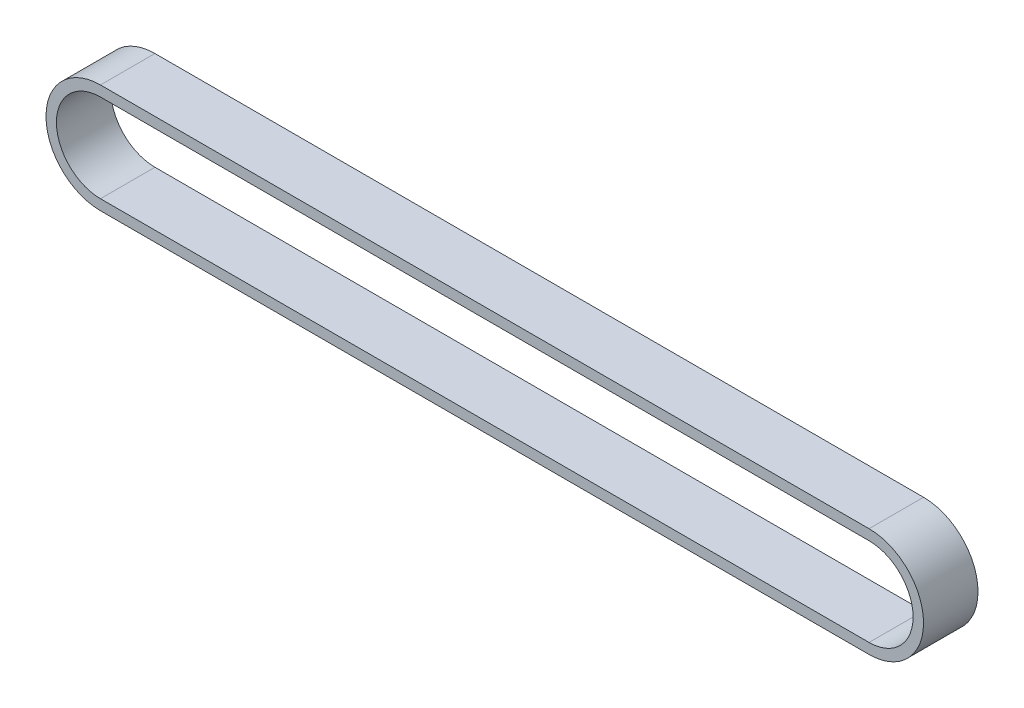
SolidWorks part; units mm, degrees
ref_plane "Front Plane" through (0, 0, 0) normal (0, 0, 1) x (1, 0, 0)
ref_plane "Top Plane" through (0, 0, 0) normal (0, 1, 0) x (1, 0, 0)
ref_plane "Right Plane" through (0, 0, 0) normal (1, 0, 0) x (0, 0, -1)
sketch "Sketch1" plane through (0, 0, 0) normal (0, 0, 1) x (1, 0, 0)
  line L0 (-43.1078, 13.5338) -> (41.5422, 13.5338) construction
  line L1 (-43.1078, 18.3838) -> (41.5422, 18.3838)
  line L2 (-43.1078, 8.6838) -> (41.5422, 8.6838)
  line L3 (-43.1078, 19.5338) -> (41.5422, 19.5338)
  line L4 (-43.1078, 7.5338) -> (41.5422, 7.5338)
  arc A0 (-43.1078, 18.3838) -> (-43.1078, 8.6838) centre (-43.1078, 13.5338) ccw
  arc A1 (41.5422, 8.6838) -> (41.5422, 18.3838) centre (41.5422, 13.5338) ccw
  arc A2 (41.5422, 7.5338) -> (41.5422, 19.5338) centre (41.5422, 13.5338) ccw
  arc A3 (-43.1078, 19.5338) -> (-43.1078, 7.5338) centre (-43.1078, 13.5338) ccw
  point P2 (-0.7828, 13.5338)
  dimension "D2" = 4.85
  dimension "D1" = 84.65
  dimension "D3" = 1.15
extrude "Boss-Extrude1" add sketch "Sketch1" along normal blind 6
